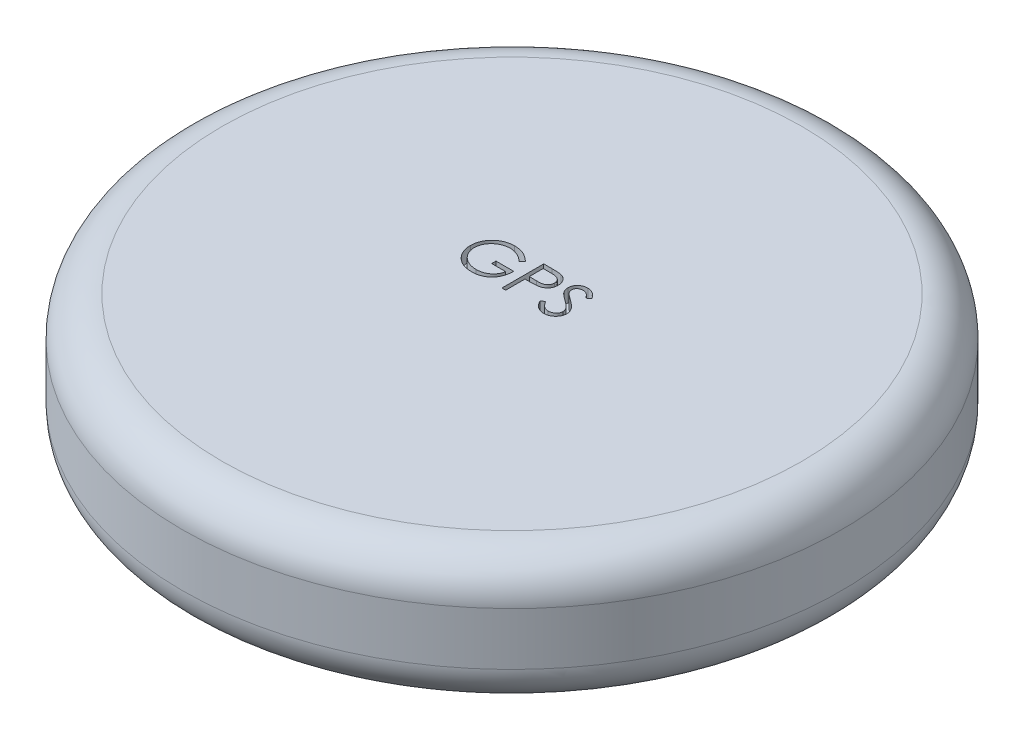
SolidWorks part; units mm, degrees
material "Custom Plastic"
ref_plane "Front Plane" through (0, 0, 0) normal (0, 0, 1) x (1, 0, 0)
ref_plane "Top Plane" through (0, 0, 0) normal (0, 1, 0) x (1, 0, 0)
ref_plane "Right Plane" through (0, 0, 0) normal (1, 0, 0) x (0, 0, -1)
sketch "Sketch2" plane through (0, 0, 0) normal (0, 1, 0) x (1, 0, 0)
  circle A0 centre (0, 0) radius 25
  dimension "D1" = 50
extrude "Boss-Extrude1" add sketch "Sketch2" along normal blind 10
fillet "Fillet1" radius 3 2 edges at (0, 0, 25) (0, 10, 25)
sketch "Sketch3" plane through (0, 0, 0) normal (0, -1, 0) x (-1, 0, 0)
  line L1 (-14.125, -14.125) -> (14.125, -14.125)
  line L2 (-14.125, -14.125) -> (-14.125, 14.125)
  line L3 (-14.125, 14.125) -> (14.125, 14.125)
  line L4 (14.125, -14.125) -> (14.125, 14.125)
  line L5 (-14.125, -14.125) -> (14.125, 14.125) construction
  line L6 (-14.125, 14.125) -> (14.125, -14.125) construction
  point P0 (0, 0)
  dimension "D1" = 28.25
extrude "Boss-Extrude2" add sketch "Sketch3" along normal blind 1
sketch "Sketch4" plane through (0, 10, 0) normal (0, 1, 0) x (1, 0, 0)
  text T0 "GPS"
  point P2 (0, 0)
  dimension "D1" = 5
extrude "Cut-Extrude1" cut sketch "Sketch4" against normal blind 1
